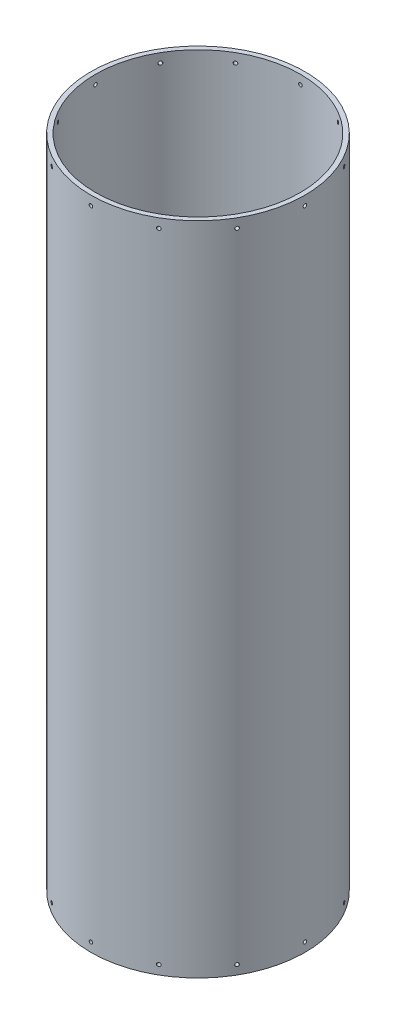
SolidWorks part; units mm, degrees
material "6061-T6 (SS)"
ref_plane "Front Plane" through (0, 0, 0) normal (0, 0, 1) x (1, 0, 0)
ref_plane "Top Plane" through (0, 0, 0) normal (0, 1, 0) x (1, 0, 0)
ref_plane "Right Plane" through (0, 0, 0) normal (1, 0, 0) x (0, 0, -1)
sketch "Sketch1" plane through (0, 0, 0) normal (0, 1, 0) x (1, 0, 0)
  circle A0 centre (0, 0) radius 142.875
  circle A1 centre (0, 0) radius 149.225
  dimension "D1" = 285.75
  dimension "D2" = 298.45
extrude "Boss-Extrude1" add sketch "Sketch1" along normal blind 914.4
ref_plane "Plane1" through (149.225, 0, 0) normal (1, 0, 0) x (0, 0, -1)
hole_wizard "#10 (0.1935) Diameter Hole1" positions "Sketch2" profile "Sketch4" hole size "#10" standard "ANSI Inch"
sketch "Sketch2" plane through (149.225, 0, 0) normal (1, 0, 0) x (0, 0, -1)
  line L0 (149.225, 914.4) -> (-149.225, 914.4) construction
  line L1 (0, 164.1475) -> (0, -164.1475) construction
  point P0 (0, 901.7)
  dimension "D1" = 12.7
sketch "Sketch4" plane through (149.225, 901.7, 0) normal (0, 1, 0) x (0, 0, -1)
  line L0 (0, 0) -> (0, 344.3972)
  line L1 (0, 344.3972) -> (2.4574, 344.3972)
  line L2 (2.4574, 344.3972) -> (2.4574, 0)
  line L5 (2.4574, 0) -> (0, 0)
  line L11 (0, -6.35) -> (0, 107.95) construction
  dimension "Thru Hole Dia." = 4.9149
  dimension "Thru Hole Depth" = 344.3972
pattern_circular "CirPattern1" count 12 over 360 about axis through (0, 914.4, 0) along (0, 1, 0) of "#10 (0.1935) Diameter Hole1"
ref_plane "Plane2" through (0, 457.2, 0) normal (0, -1, 0) x (-1, 0, 0)
mirror "Mirror1" about plane through (0, 457.2, 0) normal (0, -1, 0) of "CirPattern1", "#10 (0.1935) Diameter Hole1"
